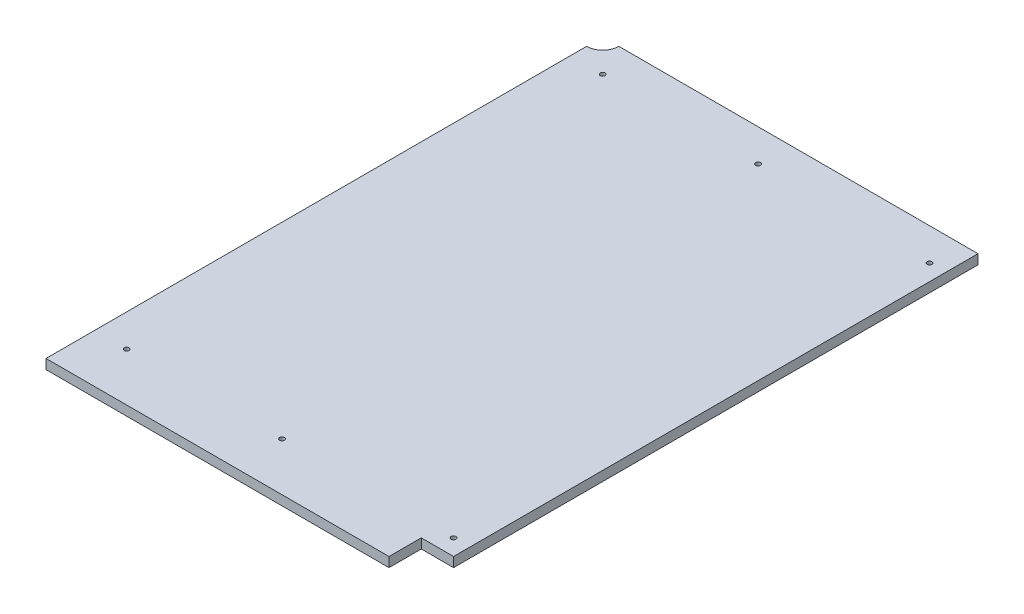
SolidWorks part; units mm, degrees
ref_plane "前视基准面" through (0, 0, 0) normal (0, 0, 1) x (1, 0, 0)
ref_plane "上视基准面" through (0, 0, 0) normal (0, 1, 0) x (1, 0, 0)
ref_plane "右视基准面" through (0, 0, 0) normal (1, 0, 0) x (0, 0, -1)
sketch "草图1" plane through (0, 0, 0) normal (0, 1, 0) x (1, 0, 0)
  line L0 (-112.725, 93.5) -> (119.825, 93.5) construction
  line L1 (-102.725, 113.5) -> (119.825, 113.5)
  line L2 (-112.725, 103.5) -> (-112.725, -231.5)
  line L3 (-112.725, -231.5) -> (99.825, -231.5)
  line L4 (119.825, 113.5) -> (119.825, -211.5)
  line L5 (-112.725, -201.5) -> (119.825, -201.5) construction
  line L8 (99.825, -231.5) -> (99.825, -211.5)
  line L9 (99.825, -211.5) -> (119.825, -211.5)
  circle A0 centre (-92.725, 93.5) radius 1.5
  circle A1 centre (109.825, 93.5) radius 1.5
  circle A2 centre (3.55, 93.5) radius 1.5
  circle A3 centre (-92.725, -201.5) radius 1.5
  circle A4 centre (3.55, -201.5) radius 1.5
  circle A5 centre (109.825, -201.5) radius 1.5
  arc A6 (-112.725, 103.5) -> (-102.725, 113.5) centre (-112.725, 113.5) ccw
  dimension "D7" = 3
  dimension "D9" = 3
  dimension "D11" = 3
  dimension "D12" = 3
  dimension "D13" = 3
  dimension "D14" = 3
  dimension "D19" = 20
  dimension "D2" = 345
  dimension "D3" = 112.725
  dimension "D4" = 113.5
  dimension "D5" = 20
  dimension "D6" = 30
  dimension "D8" = 20
  dimension "D10" = 10
  dimension "D15" = 232.55
  dimension "D16" = 20
  dimension "D17" = 10
  dimension "D18" = 20
extrude "凸台-拉伸1" add sketch "草图1" along normal blind 6
